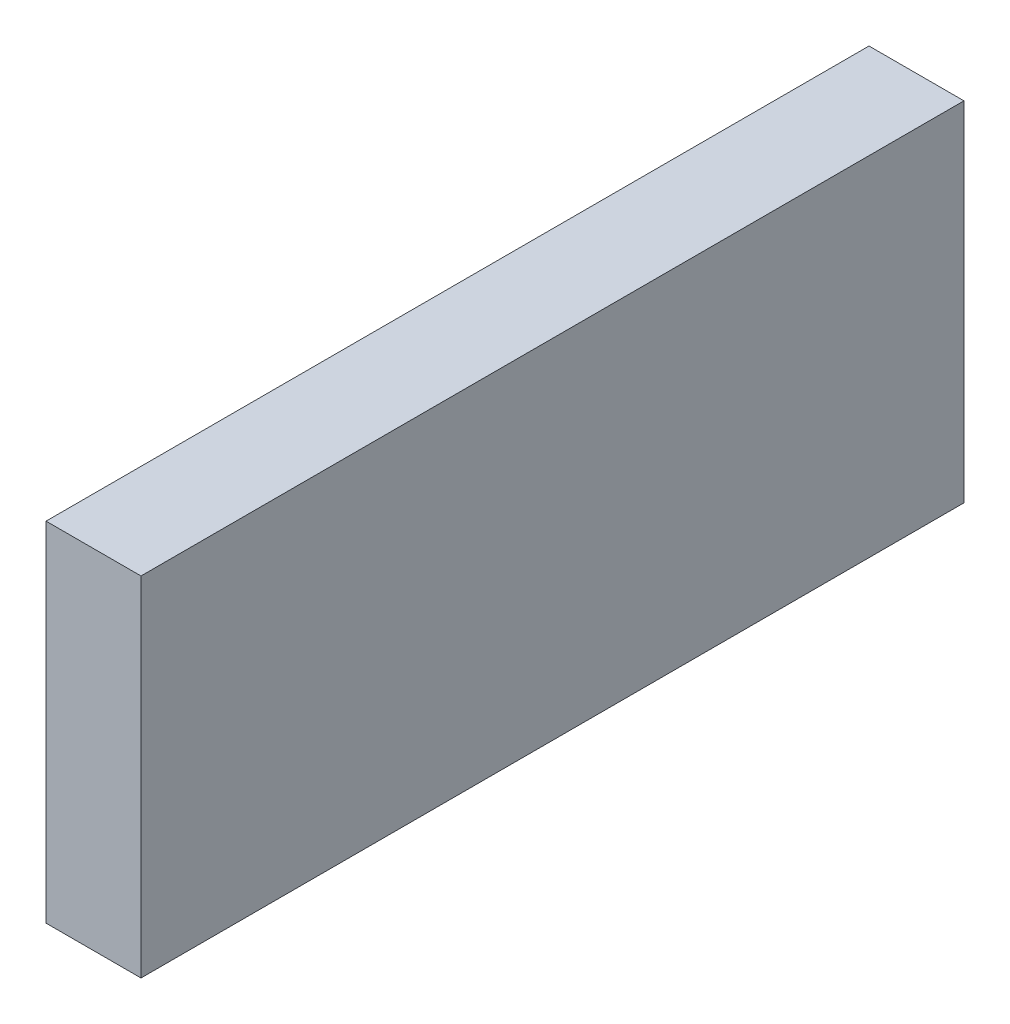
SolidWorks part; units mm, degrees
ref_plane "Front Plane" through (0, 0, 0) normal (0, 0, 1) x (1, 0, 0)
ref_plane "Top Plane" through (0, 0, 0) normal (0, 1, 0) x (1, 0, 0)
ref_plane "Right Plane" through (0, 0, 0) normal (1, 0, 0) x (0, 0, -1)
sketch "Sketch2" plane through (0, 0, 0) normal (0, 1, 0) x (1, 0, 0)
  line L1 (-15, 130) -> (15, 130)
  line L2 (-15, 130) -> (-15, -130)
  line L3 (-15, -130) -> (15, -130)
  line L4 (15, 130) -> (15, -130)
  dimension "D1" = 30
  dimension "D2" = 260
  dimension "D3" = 130
  dimension "D4" = 15
extrude "Boss-Extrude1" add sketch "Sketch2" along normal blind 110
